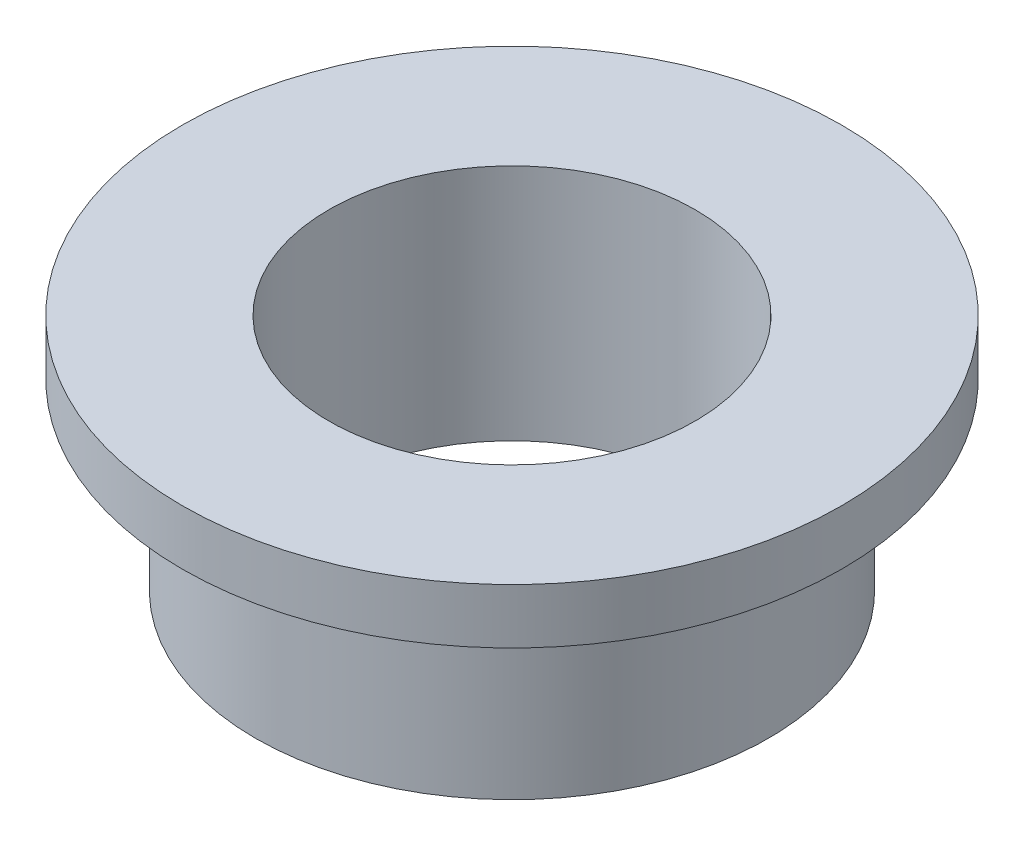
SolidWorks part; units mm, degrees
ref_plane "Front Plane" through (0, 0, 0) normal (0, 0, 1) x (1, 0, 0)
ref_plane "Top Plane" through (0, 0, 0) normal (0, 1, 0) x (1, 0, 0)
ref_plane "Right Plane" through (0, 0, 0) normal (1, 0, 0) x (0, 0, -1)
sketch "Sketch1" plane through (0, 0, 0) normal (0, 0, 1) x (1, 0, 0)
  line L0 (0, 0) -> (0, 5.4195) construction
  line L1 (5, 0) -> (5, 6.5)
  line L2 (5, 6.5) -> (9, 6.5)
  line L3 (9, 6.5) -> (9, 5)
  line L4 (9, 5) -> (7, 5)
  line L5 (7, 5) -> (7, 0)
  line L6 (7, 0) -> (5, 0)
  dimension "D1" = 14
  dimension "D2" = 10
  dimension "D3" = 1.5
  dimension "D4" = 5
  dimension "D5" = 18
revolve "Revolve1" add sketch "Sketch1" angle 360 about L0
